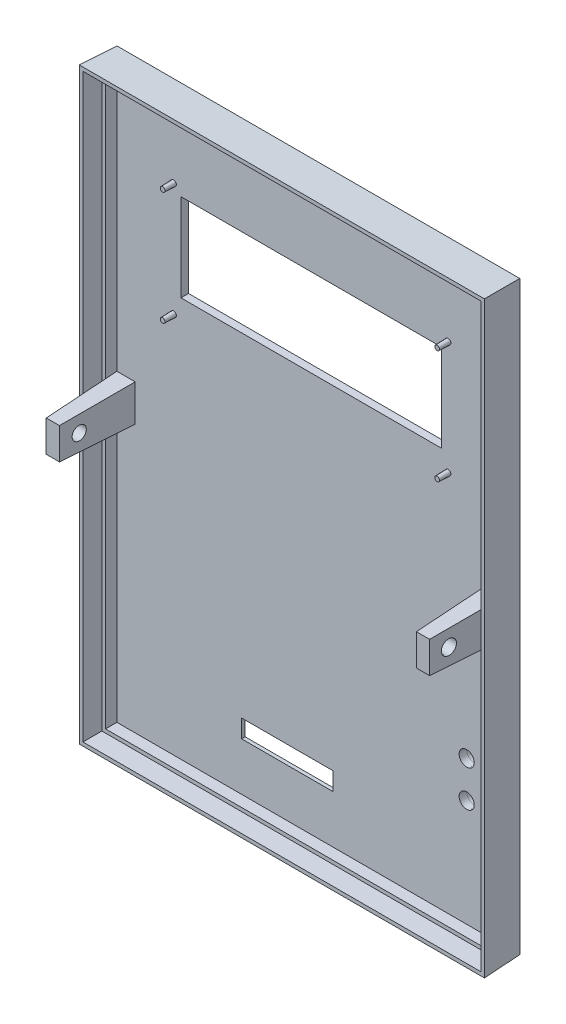
SolidWorks part; units mm, degrees
ref_plane "Front Plane" through (0, 0, 0) normal (0, 0, 1) x (1, 0, 0)
ref_plane "Top Plane" through (0, 0, 0) normal (0, 1, 0) x (1, 0, 0)
ref_plane "Right Plane" through (0, 0, 0) normal (1, 0, 0) x (0, 0, -1)
sketch "Sketch1" plane through (0, 0, 0) normal (0, 0, 1) x (1, 0, 0)
  line L1 (55, -80) -> (-55, -80)
  line L2 (55, -80) -> (55, 80)
  line L3 (55, 80) -> (-55, 80)
  line L4 (-55, -80) -> (-55, 80)
  line L5 (55, -80) -> (-55, 80) construction
  line L6 (55, 80) -> (-55, -80) construction
  point P0 (0, 0)
  dimension "D1" = 110
  dimension "D2" = 160
extrude "Boss-Extrude1" add sketch "Sketch1" along normal blind 10 draft 2 draft outward yes
shell "Shell1" thickness 2
sketch "Sketch3" plane through (0, 0, 10) normal (0, 0, 1) x (1, 0, 0)
  line L14 (54.3492, -79.3492) -> (54.3492, 79.3492)
  line L15 (-54.3492, -79.3492) -> (54.3492, -79.3492)
  line L16 (-54.3492, 79.3492) -> (-54.3492, -79.3492)
  line L17 (54.3492, 79.3492) -> (-54.3492, 79.3492)
  line L18 (54.3492, -79.3492) -> (54.3492, 79.3492)
  line L19 (-54.3492, -79.3492) -> (54.3492, -79.3492)
  line L20 (-54.3492, 79.3492) -> (-54.3492, -79.3492)
  line L21 (54.3492, 79.3492) -> (-54.3492, 79.3492)
  dimension "D1" = 1
extrude "Cut-Extrude3" cut sketch "Sketch3" against normal blind 5 draft 2
sketch "Sketch4" plane through (0, 0, 0) normal (0, 0, -1) x (-1, 0, 0)
  line L0 (-55, 80) -> (55, 80) construction
  line L1 (35.5, 31.2) -> (-35.5, 31.2)
  line L2 (35.5, 31.2) -> (35.5, 55)
  line L3 (35.5, 55) -> (-35.5, 55)
  line L4 (-35.5, 31.2) -> (-35.5, 55)
  line L5 (35.5, 31.2) -> (-35.5, 55) construction
  line L6 (35.5, 55) -> (-35.5, 31.2) construction
  line L7 (-55, -80) -> (-55, 80) construction
  point P0 (0, 43.1)
  point P9 (0, 0)
  point P10 (0, 0)
  dimension "D1" = 25
  dimension "D2" = 23.8
  dimension "D3" = 55
  dimension "D4" = 71
extrude "Cut-Extrude4" cut sketch "Sketch4" against normal up to next (2 mm away) draft 2 draft outward yes
sketch "Sketch5" plane through (0, 0, 0) normal (0, 0, -1) x (-1, 0, 0)
  line L0 (-42.5, -38.8) -> (-42.5, -48.8) construction
  line L2 (-55, -80) -> (-55, 80) construction
  line L4 (-35.5, 31.2) -> (35.5, 31.2) construction
  circle A0 centre (-42.5, -38.8) radius 3
  circle A1 centre (-42.5, -48.8) radius 3
  circle A2 centre (-42.5, -38.8) radius 2
  circle A3 centre (-42.5, -48.8) radius 2
  dimension "D3" = 6
  dimension "D4" = 6
  dimension "D6" = 4
  dimension "D7" = 4
  dimension "D1" = 10
  dimension "D2" = 70
  dimension "D5" = 12.5
extrude "Boss-Extrude2" add sketch "Sketch5" along normal blind 3 draft 2
sketch "Sketch8" plane through (0, 0, 0) normal (0, 0, -1) x (-1, 0, 0)
  circle A0 centre (-42.5, -48.8) radius 2
  circle A1 centre (-42.5, -38.8) radius 2
  dimension "D1" = 4
  dimension "D2" = 4
extrude "Cut-Extrude5" cut sketch "Sketch8" against normal up to next (2 mm away) draft 2 draft outward yes
sketch "Sketch9" plane through (0, 0, 2) normal (0, 0, 1) x (1, 0, 0)
  line L0 (-35.5698, 31.1302) -> (-35.5698, 55.0698) construction
  line L1 (39.9302, 25.1698) -> (-40.0698, 25.1698)
  line L2 (39.9302, 25.1698) -> (39.9302, 61.1698)
  line L3 (39.9302, 61.1698) -> (-40.0698, 61.1698)
  line L4 (-40.0698, 25.1698) -> (-40.0698, 61.1698)
  line L5 (39.9302, 25.1698) -> (-40.0698, 61.1698) construction
  line L6 (39.9302, 61.1698) -> (-40.0698, 25.1698) construction
  line L7 (-35.5698, 55.0698) -> (35.5698, 55.0698) construction
  point P0 (-0.0698, 43.1698)
  dimension "D1" = 80
  dimension "D2" = 36
  dimension "D3" = 35.5
  dimension "D4" = 11.9
sketch "Sketch10" plane through (0, 0, 2) normal (0, 0, 1) x (1, 0, 0)
  line L0 (39.9302, 25.1698) -> (-40.0698, 61.1698) construction
  line L1 (39.9302, 61.1698) -> (-40.0698, 25.1698) construction
  line L2 (-37.5698, 57.2948) -> (-37.5698, 26.2948) construction
  line L3 (-37.5698, 57.2948) -> (37.4302, 57.2948) construction
  line L4 (37.4302, 57.2948) -> (37.4302, 26.2948) construction
  line L5 (37.4302, 26.2948) -> (-37.5698, 26.2948) construction
  circle A0 centre (-37.5698, 57.2948) radius 0.75
  circle A1 centre (37.4302, 57.2948) radius 0.75
  circle A2 centre (37.4302, 26.2948) radius 0.75
  circle A3 centre (-37.5698, 26.2948) radius 0.75
  dimension "D3" = 1.5
  dimension "D4" = 1.5
  dimension "D5" = 1.5
  dimension "D6" = 1.5
  dimension "D1" = 75
  dimension "D2" = 31
extrude "Boss-Extrude3" add sketch "Sketch10" along normal blind 3 draft 2
sketch "Sketch13" plane through (0, 0, 2) normal (0, 0, 1) x (1, 0, 0)
  line L0 (-53.0686, 78.0686) -> (-53.0686, -78.0686) construction
  line L1 (-48.0686, 5) -> (-53.0686, 5)
  line L2 (-48.0686, 5) -> (-48.0686, -5)
  line L3 (-48.0686, -5) -> (-53.0686, -5)
  line L4 (-53.0686, 5) -> (-53.0686, -5)
  line L5 (-48.0686, 5) -> (-53.0686, -5) construction
  line L6 (-48.0686, -5) -> (-53.0686, 5) construction
  line L7 (53.0686, -78.0686) -> (53.0686, 78.0686) construction
  line L8 (48.0686, -5) -> (53.0686, -5)
  line L9 (48.0686, -5) -> (48.0686, 5)
  line L10 (48.0686, 5) -> (53.0686, 5)
  line L11 (53.0686, -5) -> (53.0686, 5)
  line L12 (48.0686, -5) -> (53.0686, 5) construction
  line L13 (48.0686, 5) -> (53.0686, -5) construction
  point P0 (-50.5686, 0)
  point P8 (50.5686, 0)
  dimension "D1" = 10
  dimension "D2" = 5
  dimension "D3" = 0
  dimension "D4" = 0
  dimension "D5" = 10
  dimension "D6" = 0
  dimension "D7" = 0
  dimension "D8" = 5
extrude "Boss-Extrude8" add sketch "Sketch13" along normal blind 20 draft 2
sketch "Sketch21" plane through (-53.0737, 0, 1.8534) normal (-0.9994, 0, 0.0349) x (0.0349, 0, 0.9994)
  line L0 (8.0622, 80.3492) -> (8.0622, -80.3492) construction
  circle A0 centre (15.0622, 0) radius 2
  dimension "D1" = 4
  dimension "D2" = 7
  dimension "D3" = 4.3016
extrude "Cut-Extrude8" cut sketch "Sketch21" against normal up to next draft 2
sketch "Sketch22" plane through (53.0737, 0, 1.8534) normal (0.9994, 0, 0.0349) x (0.0349, 0, -0.9994)
  line L0 (-8.0622, -80.3492) -> (-8.0622, 80.3492) construction
  circle A0 centre (-15.0622, 0) radius 2
  dimension "D1" = 4
  dimension "D2" = 7
  dimension "D3" = 4.3016
extrude "Cut-Extrude9" cut sketch "Sketch22" against normal up to next draft 2
sketch "Sketch27" plane through (0, 0, 0) normal (0, 0, -1) x (-1, 0, 0)
  line L0 (55, 80) -> (55, -80) construction
  line L1 (40, -69.8) -> (-29, -69.8)
  line L2 (40, -69.8) -> (40, 6.2)
  line L3 (40, 6.2) -> (-29, 6.2)
  line L4 (-29, -69.8) -> (-29, 6.2)
  line L5 (40, -69.8) -> (-29, 6.2) construction
  line L6 (40, 6.2) -> (-29, -69.8) construction
  line L7 (55, -80) -> (-55, -80) construction
  point P0 (5.5, -31.8)
  dimension "D1" = 69
  dimension "D2" = 76
  dimension "D3" = 15
  dimension "D4" = 10.2
extrude "Cut-Extrude10" cut sketch "Sketch27" against normal blind 1 draft 2
sketch "Sketch28" plane through (0, 0, 1) normal (0, 0, -1) x (-1, 0, 0)
  line L0 (-28.9651, -69.7651) -> (39.9651, -69.7651) construction
  line L1 (19.0349, -59.9651) -> (-5.9651, -59.9651)
  line L2 (19.0349, -59.9651) -> (19.0349, -64.9651)
  line L3 (19.0349, -64.9651) -> (-5.9651, -64.9651)
  line L4 (-5.9651, -59.9651) -> (-5.9651, -64.9651)
  line L5 (19.0349, -59.9651) -> (-5.9651, -64.9651) construction
  line L6 (19.0349, -64.9651) -> (-5.9651, -59.9651) construction
  line L7 (-28.9651, 6.1651) -> (-28.9651, -69.7651) construction
  point P0 (6.5349, -62.4651)
  dimension "D1" = 4.8
  dimension "D2" = 5
  dimension "D3" = 25
  dimension "D4" = 23
extrude "Cut-Extrude11" cut sketch "Sketch28" against normal up to next (1 mm away) draft 2
